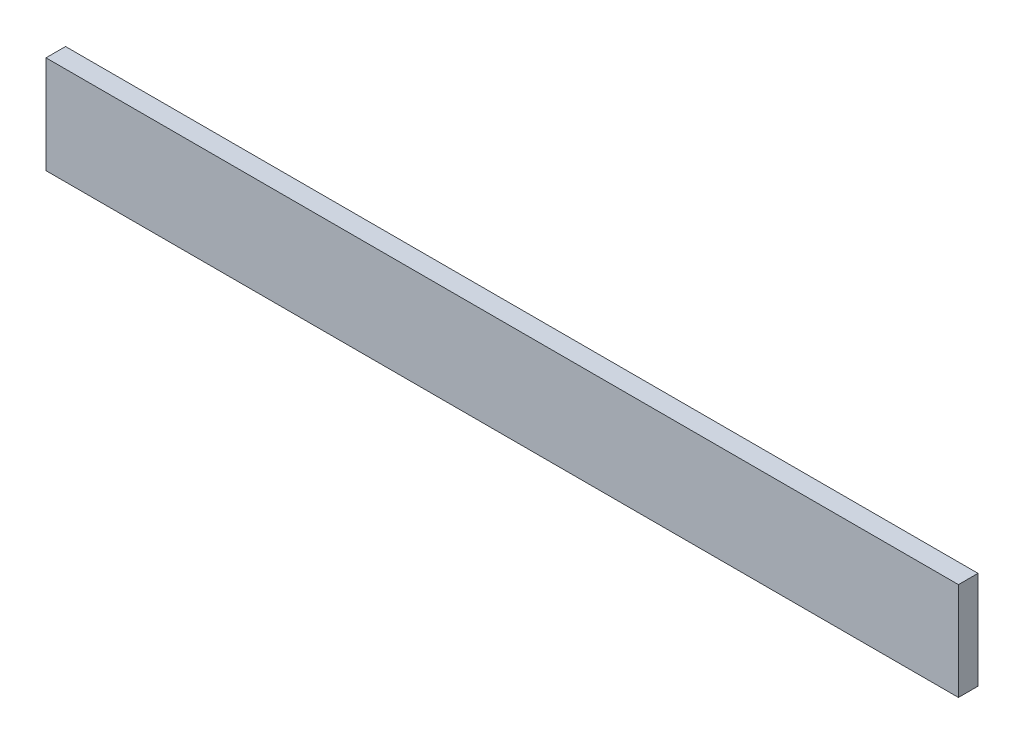
SolidWorks part; units mm, degrees
material "Polyurethane Foam Rigid"
ref_plane "Front Plane" through (0, 0, 0) normal (0, 0, 1) x (1, 0, 0)
ref_plane "Top Plane" through (0, 0, 0) normal (0, 1, 0) x (1, 0, 0)
ref_plane "Right Plane" through (0, 0, 0) normal (1, 0, 0) x (0, 0, -1)
sketch "Sketch1" plane through (0, 0, 0) normal (0, 0, 1) x (1, 0, 0)
  line L1 (-70, -7.5) -> (70, -7.5)
  line L2 (-70, -7.5) -> (-70, 7.5)
  line L3 (-70, 7.5) -> (70, 7.5)
  line L4 (70, -7.5) -> (70, 7.5)
  point P5 (-32.633, -6.7428)
  point P6 (0, 7.5)
  point P8 (70, 0)
  dimension "D1" = 15
  dimension "D2" = 140
extrude "Boss-Extrude1" add sketch "Sketch1" along normal blind 3
